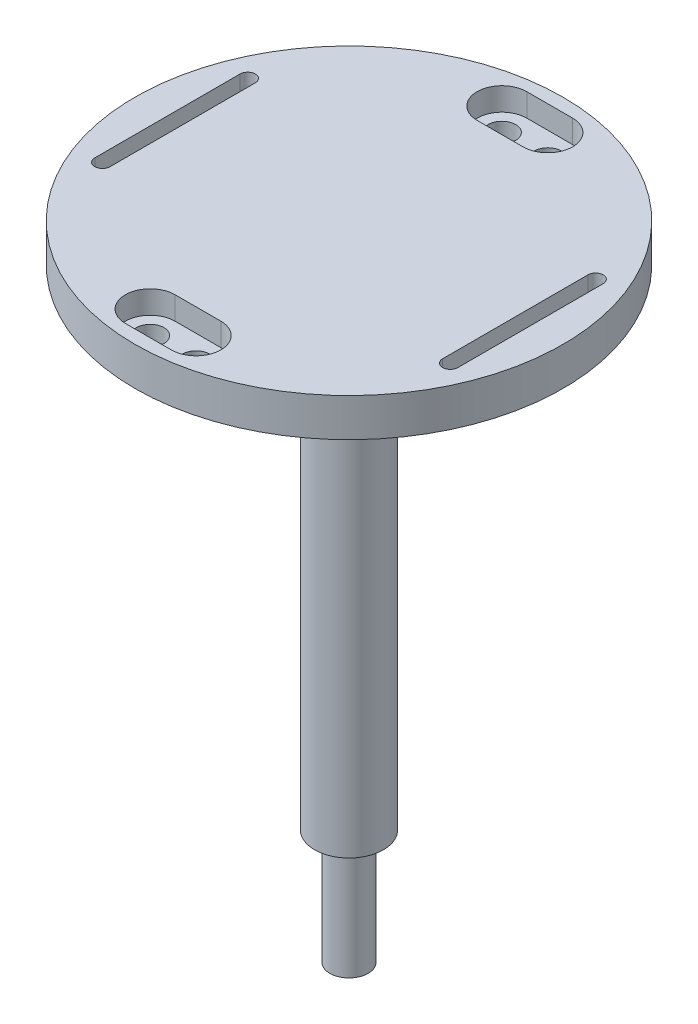
SolidWorks part; units mm, degrees
ref_plane "Front Plane" through (0, 0, 0) normal (0, 0, 1) x (1, 0, 0)
ref_plane "Top Plane" through (0, 0, 0) normal (0, 1, 0) x (1, 0, 0)
ref_plane "Right Plane" through (0, 0, 0) normal (1, 0, 0) x (0, 0, -1)
sketch "Sketch1" plane through (0, 0, 0) normal (0, 0, 1) x (1, 0, 0)
  line L0 (0, 0) -> (0, 84) construction
  line L1 (0, 84) -> (28, 84)
  line L2 (28, 84) -> (28, 79)
  line L3 (28, 79) -> (15, 79)
  line L4 (15, 79) -> (15, 80)
  line L5 (15, 80) -> (4.5, 80)
  line L6 (4.5, 80) -> (4.5, 15)
  line L7 (4.5, 15) -> (2.5, 15)
  line L8 (2.5, 15) -> (2.5, 0)
  line L9 (2.5, 0) -> (0, 0)
  line L10 (0, 0) -> (0, 84)
  dimension "D1" = 79
  dimension "D2" = 5
  dimension "D3" = 9
  dimension "D4" = 1
  dimension "D5" = 30
  dimension "D6" = 5
  dimension "D7" = 56
  dimension "D8" = 15
revolve "Revolve1" add sketch "Sketch1" angle 360 about L0
hole_wizard "CBORE for M3 SHCS1" positions "Sketch2" profile "Sketch3" counterbore size "M3" standard "ANSI Metric"
sketch "Sketch2" plane through (0, 84, 0) normal (0, 1, 0) x (1, 0, 0)
  line L0 (0, 0) -> (0, 23) construction
  line L1 (0, 23) -> (3, 23) construction
  line L3 (0, 23) -> (-3, 23) construction
  line L5 (-3, -23) -> (0, -23) construction
  line L6 (0, -23) -> (0, 0) construction
  line L8 (0, -23) -> (3, -23) construction
  point P0 (3, 23)
  point P11 (-3, 23)
  point P14 (-3, -23)
  point P21 (3, -23)
  dimension "D1" = 46
  dimension "D2" = 6
sketch "Sketch3" plane through (3, 84, -23) normal (1, 0, 0) x (0, 0, 1)
  line L0 (0, 0) -> (0, 7.5817)
  line L1 (0, 7.5817) -> (1.8, 6.5001)
  line L2 (1.8, 6.5001) -> (1.8, 3)
  line L3 (1.8, 3) -> (3.25, 3)
  line L4 (3.25, 3) -> (3.25, 0)
  line L5 (3.25, 0) -> (0, 0)
  line L10 (0, 7.5817) -> (-1.8, 6.5001) construction
  line L11 (0, -6.35) -> (0, 107.95) construction
  dimension "Hole Dia." = 3.6
  dimension "Hole Depth" = 6.5001
  dimension "C'Bore Dia." = 6.5
  dimension "C'Bore Depth" = 3
  dimension "Drill Angle" = 118
sketch "Sketch4" plane through (0, 81, 0) normal (0, 1, 0) x (1, 0, 0)
  line L0 (-3, 23) -> (3, 23) construction
  line L1 (-3, 26.25) -> (3, 26.25)
  line L2 (-3, 19.75) -> (3, 19.75)
  line L3 (-3, -23) -> (3, -23) construction
  line L4 (-3, -19.75) -> (3, -19.75)
  line L5 (-3, -26.25) -> (3, -26.25)
  arc A0 (-3, 26.25) -> (-3, 19.75) centre (-3, 23) ccw
  arc A1 (3, 19.75) -> (3, 26.25) centre (3, 23) ccw
  arc A2 (0, 21.75) -> (0, 24.25) centre (3, 23) ccw construction
  arc A3 (-3, -19.75) -> (-3, -26.25) centre (-3, -23) ccw
  arc A4 (3, -26.25) -> (3, -19.75) centre (3, -23) ccw
  arc A5 (0, -21.75) -> (0, -24.25) centre (-3, -23) ccw construction
  point P4 (0, 23)
  point P16 (0, -23)
extrude "Cut-Extrude1" cut sketch "Sketch4" along normal through all
sketch "Sketch5" plane through (0, 84, 0) normal (0, 1, 0) x (1, 0, 0)
  line L0 (-22.75, -9.5) -> (-22.75, 9.5) construction
  line L1 (-23.75, -9.5) -> (-23.75, 9.5)
  line L2 (-21.75, -9.5) -> (-21.75, 9.5)
  arc A0 (-23.75, -9.5) -> (-21.75, -9.5) centre (-22.75, -9.5) ccw
  arc A1 (-21.75, 9.5) -> (-23.75, 9.5) centre (-22.75, 9.5) ccw
  point P2 (-22.75, 0)
  point P7 (-22.7589, 9.1745)
  point P8 (0, 0)
  dimension "D1" = 22.75
  dimension "D2" = 19
  dimension "D3" = 2
extrude "Cut-Extrude2" cut sketch "Sketch5" against normal through all
mirror "Mirror1" about plane through (0, 0, 0) normal (1, 0, 0) of "Cut-Extrude2"
chamfer "Chamfer1" [suppressed] distance 0.762 angle 45
